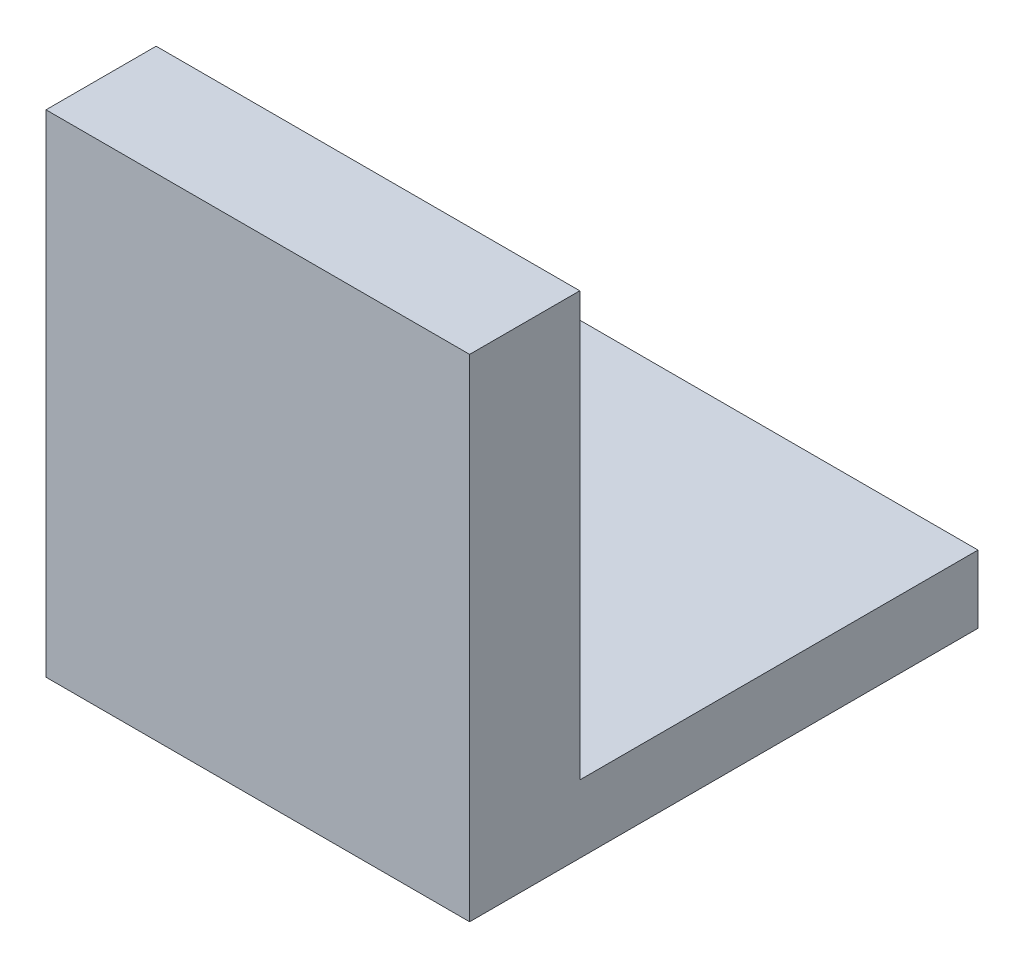
SolidWorks part; units mm, degrees
ref_plane "Front Plane" through (0, 0, 0) normal (0, 0, 1) x (1, 0, 0)
ref_plane "Top Plane" through (0, 0, 0) normal (0, 1, 0) x (1, 0, 0)
ref_plane "Right Plane" through (0, 0, 0) normal (1, 0, 0) x (0, 0, -1)
sketch "Sketch1" plane through (0, 0, 0) normal (0, 1, 0) x (1, 0, 0)
  line L1 (-25, -30) -> (25, -30)
  line L2 (-25, -30) -> (-25, 30)
  line L3 (-25, 30) -> (25, 30)
  line L4 (25, -30) -> (25, 30)
  line L5 (-25, -30) -> (25, 30) construction
  line L6 (-25, 30) -> (25, -30) construction
  point P0 (0, 0)
  dimension "D1" = 50
  dimension "D2" = 60
extrude "Boss-Extrude1" add sketch "Sketch1" along normal blind 8
sketch "Sketch2" plane through (0, 8, 0) normal (0, 1, 0) x (1, 0, 0)
  line L0 (25, -30) -> (25, 30) construction
  line L1 (-25, -30) -> (25, -30)
  line L2 (-25, -30) -> (-25, -17)
  line L3 (-25, -17) -> (25, -17)
  line L4 (25, -30) -> (25, -17)
  dimension "D1" = 13
extrude "Boss-Extrude2" add sketch "Sketch2" along normal blind 50
